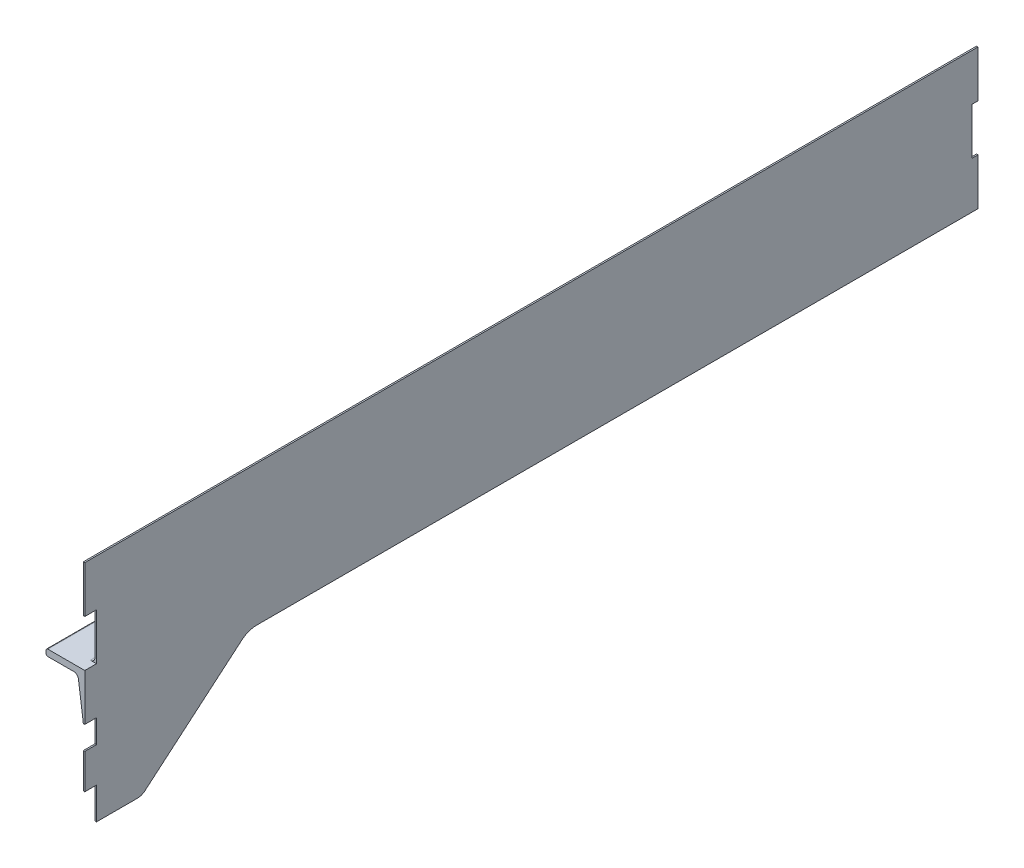
SolidWorks part; units mm, degrees
material "S-Glass Fiber"
ref_plane "Front Plane" through (0, 0, 0) normal (0, 0, 1) x (1, 0, 0)
ref_plane "Top Plane" through (0, 0, 0) normal (0, 1, 0) x (1, 0, 0)
ref_plane "Right Plane" through (0, 0, 0) normal (1, 0, 0) x (0, 0, -1)
ref_plane "Plane1" through (-94.488, 0, 0) normal (-1, 0, 0) x (0, -1, 0)
sketch "Sketch1" plane through (-94.488, 0, 0) normal (-1, 0, 0) x (0, -1, 0)
  line L4 (111.125, -203.2) -> (85.725, -203.2)
  line L5 (85.725, -203.2) -> (85.725, -196.85)
  line L6 (85.725, -196.85) -> (60.325, -196.85)
  line L7 (60.325, -196.85) -> (60.325, -682.625)
  line L8 (60.325, -682.625) -> (85.725, -682.625)
  line L9 (85.725, -682.625) -> (85.725, -679.45)
  line L10 (85.725, -679.45) -> (111.125, -679.45)
  line L11 (111.125, -679.45) -> (111.125, -682.625)
  line L12 (111.125, -682.625) -> (136.525, -682.625)
  line L13 (136.525, -682.625) -> (136.525, -196.85)
  line L14 (136.525, -196.85) -> (111.125, -196.85)
  line L15 (111.125, -196.85) -> (111.125, -203.2)
  line L16 (136.525, -196.85) -> (185.6232, -196.85) construction
  line L17 (185.6232, -196.85) -> (185.6232, -227.7965) construction
  line L18 (184.1182, -229.5729) -> (139.535, -282.1971)
  line L19 (136.525, -203.2) -> (149.225, -203.2)
  line L20 (149.225, -203.2) -> (149.225, -196.85)
  line L21 (168.275, -196.85) -> (168.275, -203.2)
  line L22 (168.275, -203.2) -> (185.6232, -203.2)
  line L23 (185.6232, -203.2) -> (185.6232, -225.4683)
  line L24 (168.275, -196.85) -> (149.225, -196.85)
  circle A0 centre (130.175, -666.75) radius 1.7526 construction
  circle A1 centre (130.175, -615.95) radius 1.7526 construction
  circle A2 centre (130.175, -565.15) radius 1.7526 construction
  circle A3 centre (130.175, -514.35) radius 1.7526 construction
  circle A4 centre (130.175, -463.55) radius 1.7526 construction
  circle A5 centre (130.175, -412.75) radius 1.7526 construction
  circle A6 centre (130.175, -361.95) radius 1.7526 construction
  circle A7 centre (130.175, -311.15) radius 1.7526 construction
  circle A8 centre (130.175, -260.35) radius 1.7526 construction
  circle A9 centre (130.175, -209.55) radius 1.7526 construction
  arc A10 (184.1182, -229.5729) -> (185.6232, -225.4683) centre (179.2732, -225.4683) ccw
  arc A11 (139.535, -282.1971) -> (136.525, -290.4065) centre (149.225, -290.4065) ccw
  point P38 (136.525, -285.75)
  dimension "D14" = 12.7
  dimension "D15" = 6.35
  dimension "D2" = 485.775
  dimension "D3" = 76.2
  dimension "D4" = 3.175
  dimension "D5" = 6.35
  dimension "D6" = 25.4
  dimension "D7" = 25.4
  dimension "D9" = 49.0982
  dimension "D10" = 82.55
  dimension "D11" = 40.271
  dimension "D12" = 19.05
  dimension "D13" = 12.7
extrude "Boss-Extrude1" add sketch "Sketch1" against normal blind 0.7937
sketch "Sketch4" plane through (0, 0, -679.45) normal (0, 0, -1) x (-1, 0, 0)
  line L0 (97.1661, -116.8229) -> (94.488, -136.525)
  line L1 (97.028, -111.125) -> (113.7935, -111.125)
  line L2 (94.488, -111.125) -> (94.488, -114.2531)
  line L3 (99.683, -114.625) -> (113.7935, -114.625)
  line L4 (114.7935, -112.125) -> (114.7935, -113.625)
  line L5 (94.488, -136.525) -> (94.488, -114.2531)
  line L10 (94.488, -111.125) -> (94.488, -108.585)
  arc A0 (97.1661, -116.8229) -> (99.683, -114.625) centre (99.683, -117.165) cw
  arc A1 (94.488, -108.585) -> (97.028, -111.125) centre (97.028, -108.585) ccw
  arc A2 (113.7935, -114.625) -> (114.7935, -113.625) centre (113.7935, -113.625) ccw
  arc A3 (113.7935, -111.125) -> (114.7935, -112.125) centre (113.7935, -112.125) cw
  point P9 (97.4649, -114.625)
  dimension "D3" = 2.54
  dimension "D4" = 2.54
  dimension "D1" = 1
  dimension "D2" = 3
extrude "Boss-Extrude2" add sketch "Sketch4" against normal blind 482.6
sketch "Sketch5" plane through (-93.6942, 0, 0) normal (1, 0, 0) x (0, 0, -1)
  line L1 (203.2, -111.125) -> (172.9789, -111.125)
  line L2 (203.2, -111.125) -> (203.2, -106.4235)
  line L3 (203.2, -106.4235) -> (172.9789, -106.4235)
  line L4 (172.9789, -111.125) -> (172.9789, -106.4235)
extrude "Cut-Extrude1" cut sketch "Sketch5" against normal blind 27.94
